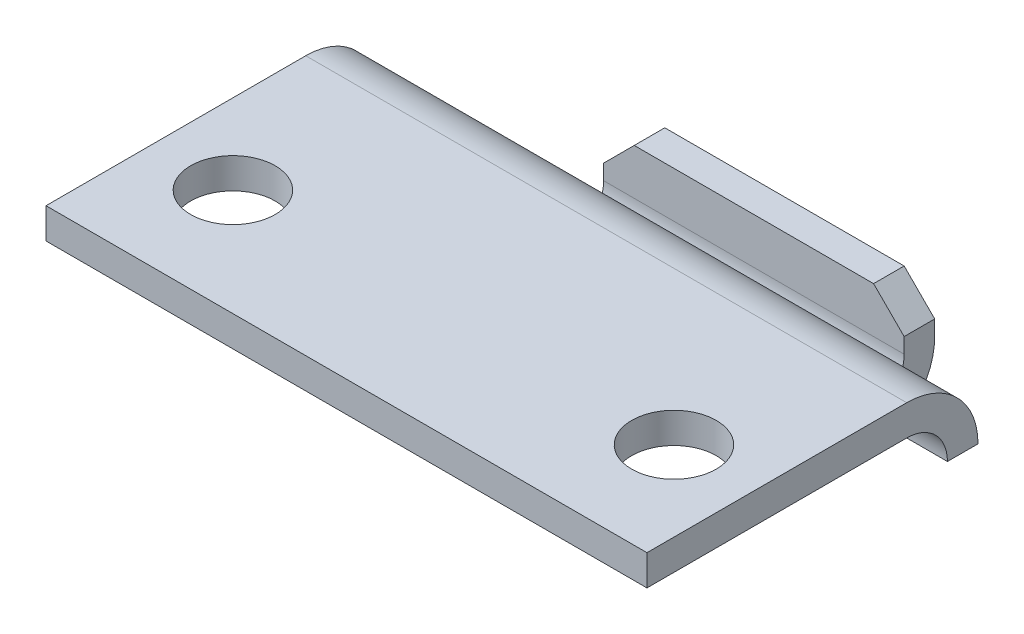
SolidWorks part; units mm, degrees
ref_plane "Front Plane" through (0, 0, 0) normal (0, 0, 1) x (1, 0, 0)
ref_plane "Top Plane" through (0, 0, 0) normal (0, 1, 0) x (1, 0, 0)
ref_plane "Right Plane" through (0, 0, 0) normal (1, 0, 0) x (0, 0, -1)
sketch "Sketch2" plane through (0, 0, 0) normal (1, 0, 0) x (0, 0, -1)
  line L0 (-5.334, 0) -> (7.62, 0)
  line L1 (9.652, -2.032) -> (9.652, -3.81)
  line L2 (16.51, -3.81) -> (16.51, -1.524)
  line L3 (14.986, -3.81) -> (14.986, -1.524)
  line L4 (11.176, -2.032) -> (11.176, -3.81)
  line L5 (-5.334, 1.524) -> (7.62, 1.524)
  line L6 (-5.334, 1.524) -> (-5.334, 0)
  line L7 (14.986, -1.524) -> (16.51, -1.524)
  arc A0 (9.652, -3.81) -> (16.51, -3.81) centre (13.081, -3.81) ccw
  arc A1 (7.62, 0) -> (9.652, -2.032) centre (7.62, -2.032) cw
  arc A2 (11.176, -3.81) -> (14.986, -3.81) centre (13.081, -3.81) ccw
  arc A3 (7.62, 1.524) -> (11.176, -2.032) centre (7.62, -2.032) cw
  point P8 (9.652, 0)
  dimension "D4" = 3.429
  dimension "D5" = 2.032
  dimension "D1" = 13.081
  dimension "D2" = 9.652
  dimension "D3" = 14.986
  dimension "D6" = 1.778
  dimension "D7" = 2.286
  dimension "D9" = 3.048
  dimension "D8" = 1.524
extrude "Extrude1" add sketch "Sketch2" along normal mid plane 29.972
sketch "Sketch3" plane through (0, 0, 0) normal (0, 0, 1) x (1, 0, 0)
  line L0 (0, 0) -> (0, 6.0295) construction
  line L1 (-17.6192, -2.032) -> (-17.6192, -11.558)
  line L2 (7.493, -2.032) -> (17.6192, -2.032)
  line L3 (7.493, -2.032) -> (7.493, -11.558)
  line L4 (7.493, -11.558) -> (17.6192, -11.558)
  line L5 (17.6192, -2.032) -> (17.6192, -11.558)
  line L6 (-7.493, -11.558) -> (-17.6192, -11.558)
  line L7 (-7.493, -2.032) -> (-7.493, -11.558)
  line L8 (-7.493, -2.032) -> (-17.6192, -2.032)
  line L9 (14.986, 1.524) -> (-14.986, 1.524) construction
  dimension "D1" = 3.556
  dimension "D2" = 14.986
extrude "Cut-Extrude1" cut sketch "Sketch3" against normal through all
sketch "Sketch4" plane through (0, 0, 0) normal (0, 1, 0) x (1, 0, 0)
  line L0 (7.493, 11.176) -> (7.493, 14.986) construction
  line L1 (-18.8312, 19.8305) -> (-7.493, 19.8305)
  line L2 (-18.8312, 19.8305) -> (-18.8312, 13.6502)
  line L3 (-18.8312, 13.6502) -> (-7.493, 13.6502)
  line L4 (-7.493, 19.8305) -> (-7.493, 13.6502)
  line L5 (7.493, 20.0628) -> (16.5078, 20.0628)
  line L6 (7.493, 20.0628) -> (7.493, 13.0926)
  line L7 (7.493, 13.0926) -> (16.5078, 13.0926)
  line L8 (16.5078, 20.0628) -> (16.5078, 13.0926)
  line L9 (-7.493, 14.986) -> (-7.493, 11.176) construction
extrude "Cut-Extrude2" cut sketch "Sketch4" against normal through all
chamfer "Chamfer1" distance 1.524 angle 45 2 edges at (7.493, -1.524, -15.748) (-7.493, -1.524, -15.748)
sketch "Sketch5" plane through (0, 0, 0) normal (0, 1, 0) x (1, 0, 0)
  line L0 (0, 0) -> (0, -7.1424) construction
  circle A0 centre (10.9982, 0) radius 2.1082
  circle A1 centre (-10.9982, 0) radius 2.1082
  dimension "D2" = 4.2164
  dimension "D1" = 21.9964
extrude "Cut-Extrude3" cut sketch "Sketch5" along normal through all
